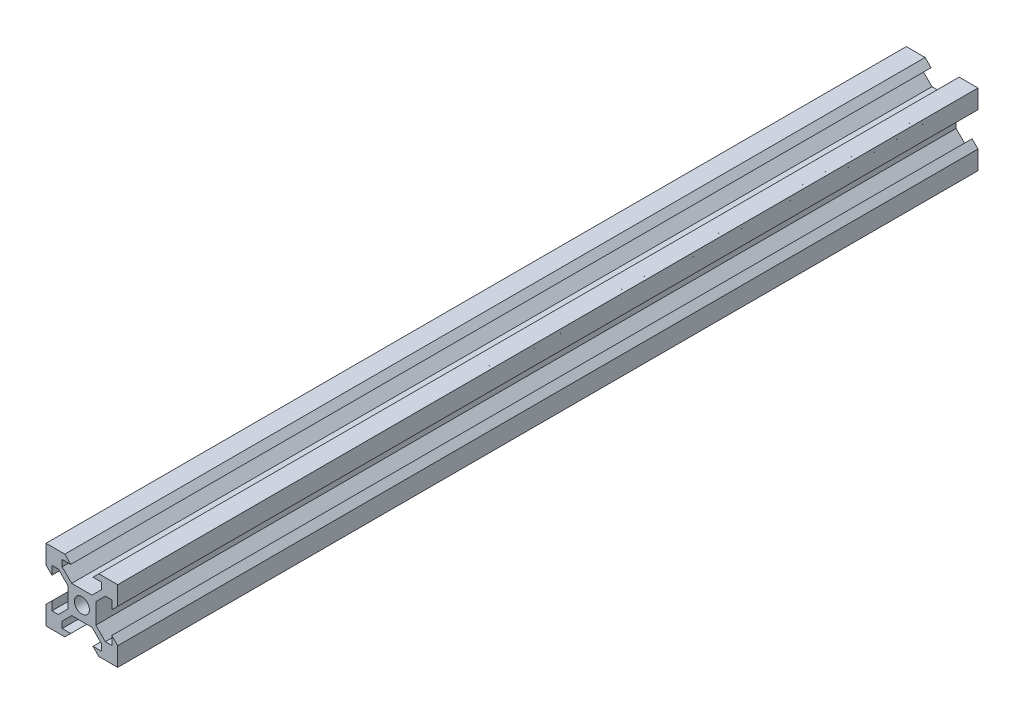
SolidWorks part; units mm, degrees
material "6061-T6 (SS)"
ref_plane "Front Plane" through (0, 0, 0) normal (0, 0, 1) x (1, 0, 0)
ref_plane "Top Plane" through (0, 0, 0) normal (0, 1, 0) x (1, 0, 0)
ref_plane "Right Plane" through (0, 0, 0) normal (1, 0, 0) x (0, 0, -1)
sketch "Sketch1" plane through (0, 0, 0) normal (0, 0, 1) x (1, 0, 0)
  line L0 (2.8343, 3.894) -> (5.5, 6.5588)
  line L1 (2.8343, -3.894) -> (-2.8343, -3.894)
  line L2 (3.8948, -2.8332) -> (3.8948, 2.8332)
  line L3 (2.8343, 3.894) -> (-2.8343, 3.894)
  line L4 (-3.8948, -2.8332) -> (-3.8948, 2.8332)
  line L5 (3.8994, -3.9006) -> (-3.8994, 3.9006) construction
  line L6 (3.9006, 3.8994) -> (-3.9006, -3.8994) construction
  line L7 (10, 4.747) -> (10, 9.9986)
  line L8 (5.5, 6.5588) -> (5.5, 8.3491)
  line L9 (5.5, 8.3491) -> (3.1, 8.3491)
  line L10 (3.1, 8.3491) -> (4.75, 9.9986)
  line L11 (4.75, 9.9986) -> (10, 9.9986)
  line L12 (8.35, 3.0975) -> (10, 4.747)
  line L13 (8.3507, 5.4975) -> (8.35, 3.0975)
  line L14 (6.5605, 5.498) -> (8.3507, 5.4975)
  line L15 (3.8948, 2.8332) -> (6.5605, 5.498)
  line L16 (0, -55) -> (0, 55) construction
  line L17 (-3.8948, 2.8332) -> (-6.5605, 5.498)
  line L18 (-6.5605, 5.498) -> (-8.3507, 5.4975)
  line L19 (-8.3507, 5.4975) -> (-8.35, 3.0975)
  line L20 (-8.35, 3.0975) -> (-10, 4.747)
  line L21 (-4.75, 9.9986) -> (-10, 9.9986)
  line L22 (-3.1, 8.3491) -> (-4.75, 9.9986)
  line L23 (-5.5, 8.3491) -> (-3.1, 8.3491)
  line L24 (-5.5, 6.5588) -> (-5.5, 8.3491)
  line L25 (-10, 4.747) -> (-10, 9.9986)
  line L26 (-2.8343, 3.894) -> (-5.5, 6.5588)
  line L27 (55, 0) -> (-55, 0) construction
  line L28 (3.8948, -2.8332) -> (6.5605, -5.498)
  line L29 (2.8343, -3.894) -> (5.5, -6.5588)
  line L30 (-3.8948, -2.8332) -> (-6.5605, -5.498)
  line L31 (-2.8343, -3.894) -> (-5.5, -6.5588)
  line L32 (-8.3507, -5.4975) -> (-8.35, -3.0975)
  line L33 (-8.35, -3.0975) -> (-10, -4.747)
  line L34 (8.3507, -5.4975) -> (8.35, -3.0975)
  line L35 (8.35, -3.0975) -> (10, -4.747)
  line L36 (-10, -4.747) -> (-10, -9.9986)
  line L37 (-5.5, -6.5588) -> (-5.5, -8.3491)
  line L38 (-5.5, -8.3491) -> (-3.1, -8.3491)
  line L39 (-3.1, -8.3491) -> (-4.75, -9.9986)
  line L40 (-4.75, -9.9986) -> (-10, -9.9986)
  line L41 (-6.5605, -5.498) -> (-8.3507, -5.4975)
  line L42 (6.5605, -5.498) -> (8.3507, -5.4975)
  line L43 (4.75, -9.9986) -> (10, -9.9986)
  line L44 (3.1, -8.3491) -> (4.75, -9.9986)
  line L45 (5.5, -8.3491) -> (3.1, -8.3491)
  line L46 (5.5, -6.5588) -> (5.5, -8.3491)
  line L47 (10, -4.747) -> (10, -9.9986)
  circle A0 centre (0, 0) radius 2.1
  point P0 (0, 0)
  dimension "D6" = 4.2
  dimension "D1" = 7.8
  dimension "D2" = 20
  dimension "D3" = 11
  dimension "D4" = 9.5
  dimension "D5" = 6.2
  dimension "D7" = 1.5
extrude "Boss-Extrude1" add sketch "Sketch1" along normal mid plane 240
